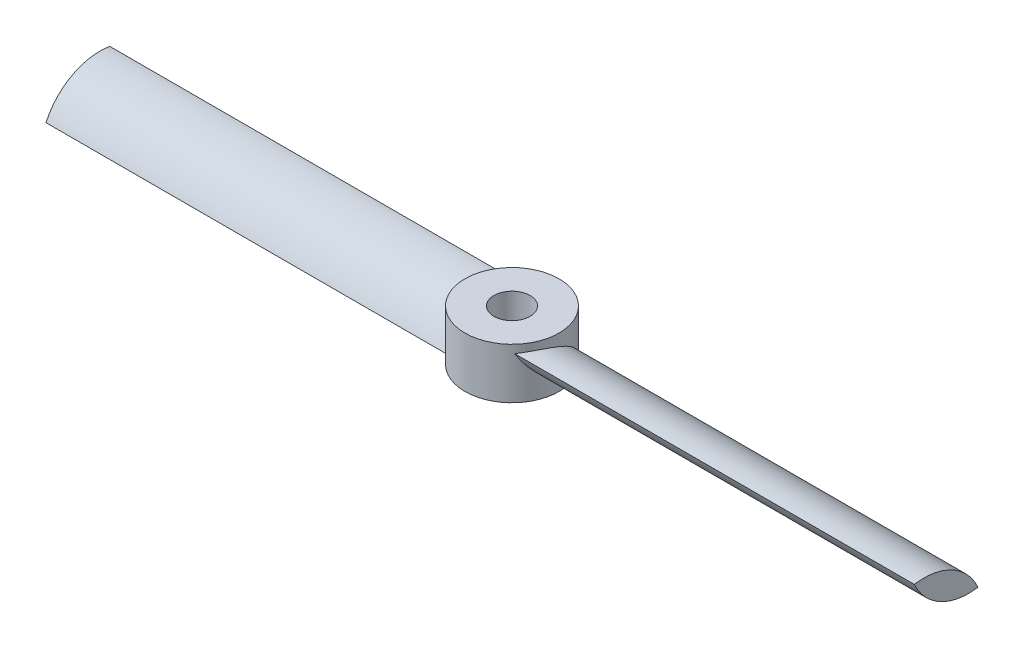
SolidWorks part; units mm, degrees
ref_plane "Front Plane" through (0, 0, 0) normal (0, 0, 1) x (1, 0, 0)
ref_plane "Top Plane" through (0, 0, 0) normal (0, 1, 0) x (1, 0, 0)
ref_plane "Right Plane" through (0, 0, 0) normal (1, 0, 0) x (0, 0, -1)
sketch "Sketch1" plane through (0, 0, 0) normal (0, 1, 0) x (1, 0, 0)
  circle A0 centre (0, 0) radius 6.5
  circle A1 centre (0, 0) radius 2.5
  dimension "D1" = 13
  dimension "D2" = 5
extrude "Boss-Extrude1" add sketch "Sketch1" along normal blind 7
sketch "Sketch2" plane through (0, 0, 0) normal (1, 0, 0) x (0, 0, -1)
  line L0 (-6.5, 7) -> (6.5, 0) construction
  line L1 (-4.4024, 5.8705) -> (4.4024, 1.1295)
  line L2 (-5.2083, 4.3737) -> (3.5964, -0.3673) construction
  line L3 (-5.2083, 4.3737) -> (-3.5964, 7.3673) construction
  line L4 (3.5964, -0.3673) -> (5.2083, 2.6263) construction
  line L5 (-3.5964, 7.3673) -> (5.2083, 2.6263) construction
  line L6 (-5.2083, 4.3737) -> (5.2083, 2.6263) construction
  line L7 (3.5964, -0.3673) -> (-3.5964, 7.3673) construction
  arc A0 (-4.4024, 5.8705) -> (4.4024, 1.1295) centre (-3.083, -2.2257) cw
  arc A1 (-4.4024, 5.8705) -> (4.4024, 1.1295) centre (3.083, 9.2257) ccw
  point P0 (-6.5, 7)
  point P1 (6.5, 0)
  point P6 (0, 3.5)
  point P7 (0.806, 4.9968)
  point P10 (0, 3.5)
  point P11 (0, 3.5)
  dimension "D1" = 10
  dimension "D2" = 3.4
extrude "Boss-Extrude2" add sketch "Sketch2" along normal blind 56 from offset 4 contours A0 L1 | L1 A1
sketch "Sketch3" plane through (0, 0, 0) normal (1, 0, 0) x (0, 0, -1)
  line L0 (0, 7.7668) -> (0, -0.5659) construction
pattern_circular "CirPattern1" count 2 over 360 about axis through (0, 7.7668, 0) along (0, -1, 0) of "Boss-Extrude2"
